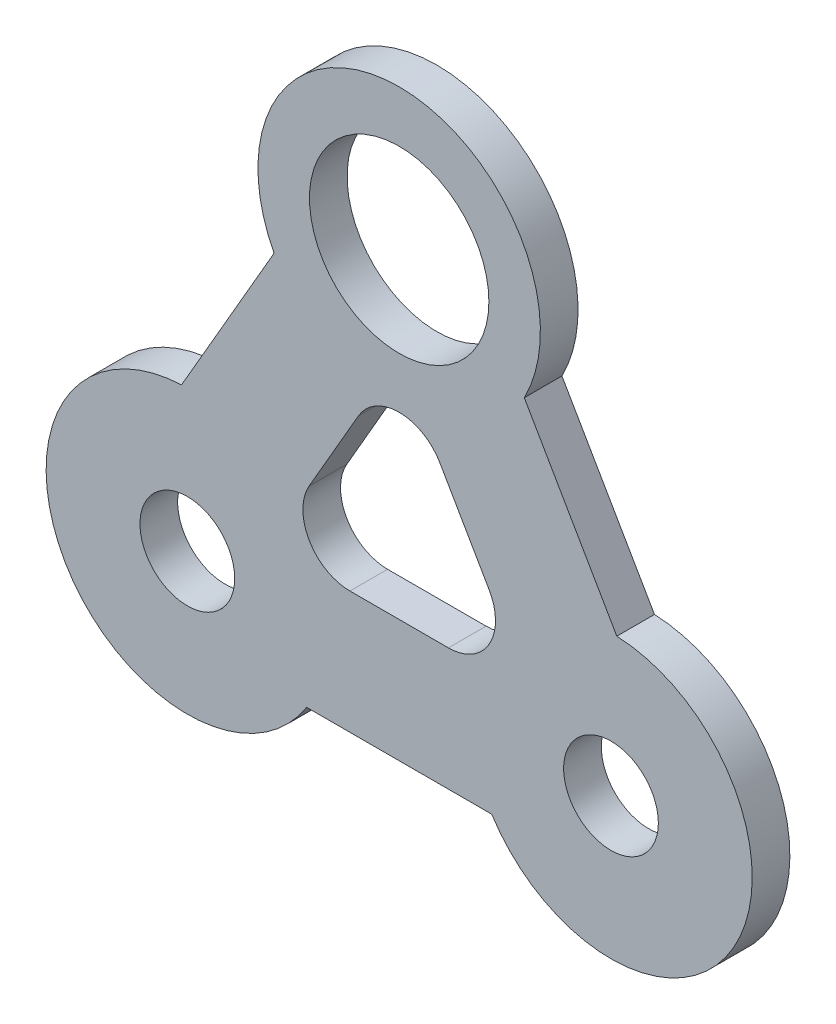
SolidWorks part; units mm, degrees
ref_plane "前视基准面" through (0, 0, 0) normal (0, 0, 1) x (1, 0, 0)
ref_plane "上视基准面" through (0, 0, 0) normal (0, 1, 0) x (1, 0, 0)
ref_plane "右视基准面" through (0, 0, 0) normal (1, 0, 0) x (0, 0, -1)
sketch "草图1" plane through (0, 0, 0) normal (0, 0, 1) x (1, 0, 0)
  line L0 (-18.4946, 4.743) -> (-23.4095, -3.7697)
  line L1 (-18.4946, 4.743) -> (-13.5798, 13.2557)
  line L2 (-0.2914, -26.7859) -> (9.5382, -26.7859)
  line L3 (-0.2914, -26.7859) -> (-10.1211, -26.7859)
  line L4 (17.9118, 4.743) -> (12.9969, 13.2557)
  line L5 (17.9118, 4.743) -> (22.8266, -3.7697)
  line L6 (9.2682, -6.2859) -> (4.0387, 2.7719)
  line L7 (-4.6216, 2.7719) -> (-9.851, -6.2859)
  line L8 (4.938, -13.7859) -> (-5.5209, -13.7859)
  circle A0 centre (-0.2914, 20.2141) radius 9.53
  circle A1 centre (22.2086, -18.757) radius 5.03
  circle A2 centre (-22.7914, -18.757) radius 5.03
  circle A3 centre (-0.2914, 0.2719) radius 5 construction
  circle A4 centre (4.938, -8.7859) radius 5 construction
  circle A5 centre (-5.5209, -8.7859) radius 5 construction
  circle A6 centre (-0.2914, 20.2141) radius 15 construction
  circle A7 centre (22.2086, -18.757) radius 15 construction
  circle A8 centre (-22.7914, -18.757) radius 15 construction
  arc A9 (12.9969, 13.2557) -> (-13.5798, 13.2557) centre (-0.2914, 20.2141) ccw
  arc A10 (22.8266, -3.7697) -> (9.5382, -26.7859) centre (22.2086, -18.757) cw
  arc A11 (-10.1211, -26.7859) -> (-23.4095, -3.7697) centre (-22.7914, -18.757) cw
  arc A12 (-5.5209, -13.7859) -> (-9.851, -6.2859) centre (-5.5209, -8.7859) cw
  arc A13 (4.938, -13.7859) -> (9.2682, -6.2859) centre (4.938, -8.7859) ccw
  arc A14 (4.0387, 2.7719) -> (-4.6216, 2.7719) centre (-0.2914, 0.2719) ccw
extrude "凸台-拉伸1" add sketch "草图1" along normal blind 4
